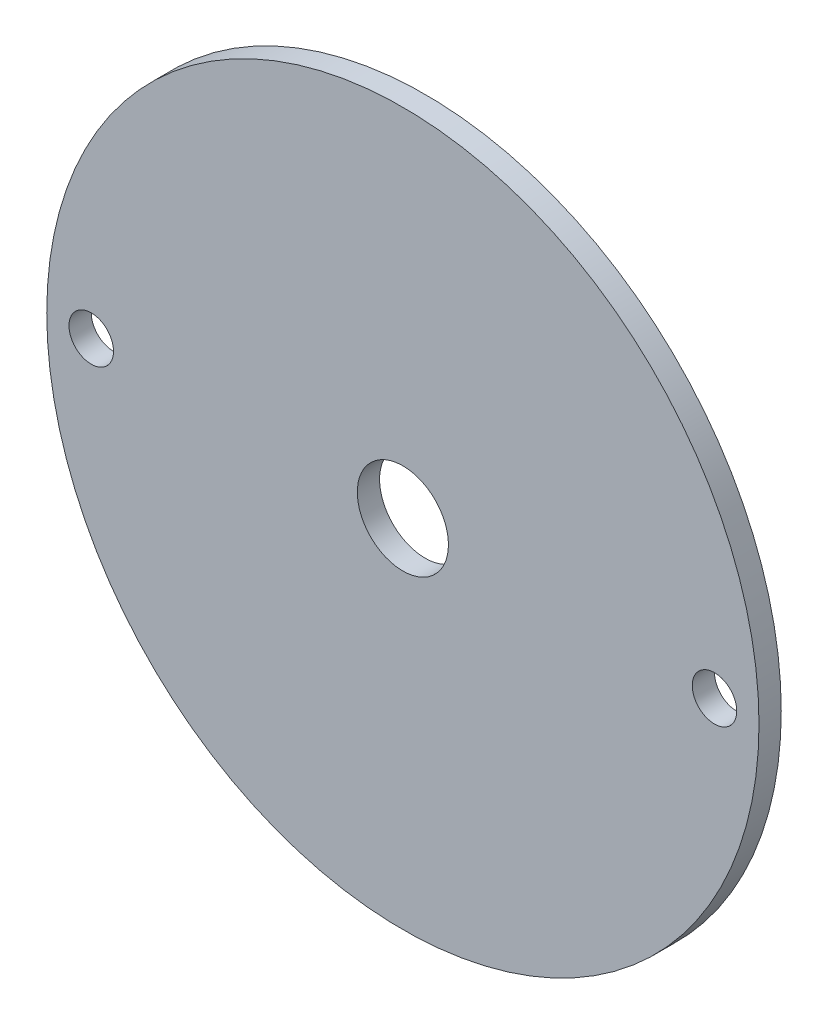
SolidWorks part; units mm, degrees
material "ABS"
ref_plane "Front Plane" through (0, 0, 0) normal (0, 0, 1) x (1, 0, 0)
ref_plane "Top Plane" through (0, 0, 0) normal (0, 1, 0) x (1, 0, 0)
ref_plane "Right Plane" through (0, 0, 0) normal (1, 0, 0) x (0, 0, -1)
sketch "Sketch1" plane through (0, 0, 0) normal (0, 0, 1) x (1, 0, 0)
  circle A0 centre (0, 0) radius 50.8
  circle A1 centre (0, 0) radius 44.45 construction
  circle A2 centre (44.45, 0) radius 3.175
  circle A3 centre (-44.45, 0) radius 3.175
  circle A4 centre (0, 0) radius 6.5
  dimension "D1" = 101.6
  dimension "D2" = 88.9
  dimension "D3" = 6.35
  dimension "D4" = 13
extrude "Boss-Extrude1" add sketch "Sketch1" along normal blind 3.175
sketch "Sketch2" plane through (0, 0, 3.175) normal (0, 0, 1) x (1, 0, 0)
  line L1 (-3.302, 38.1) -> (3.302, 38.1)
  line L2 (-3.302, 38.1) -> (-3.302, 40.64)
  line L3 (-3.302, 40.64) -> (3.302, 40.64)
  line L4 (3.302, 38.1) -> (3.302, 40.64)
  line L5 (0, 40.64) -> (0, 38.1) construction
  line L6 (-3.302, 39.37) -> (3.302, 39.37) construction
  circle A1 centre (0, 0) radius 39.37 construction
  point P2 (0, 39.37)
  dimension "D1" = 78.74
  dimension "D2" = 6.604
  dimension "D3" = 2.54
extrude "Cut-Extrude1" [suppressed] cut sketch "Sketch2" against normal through all
